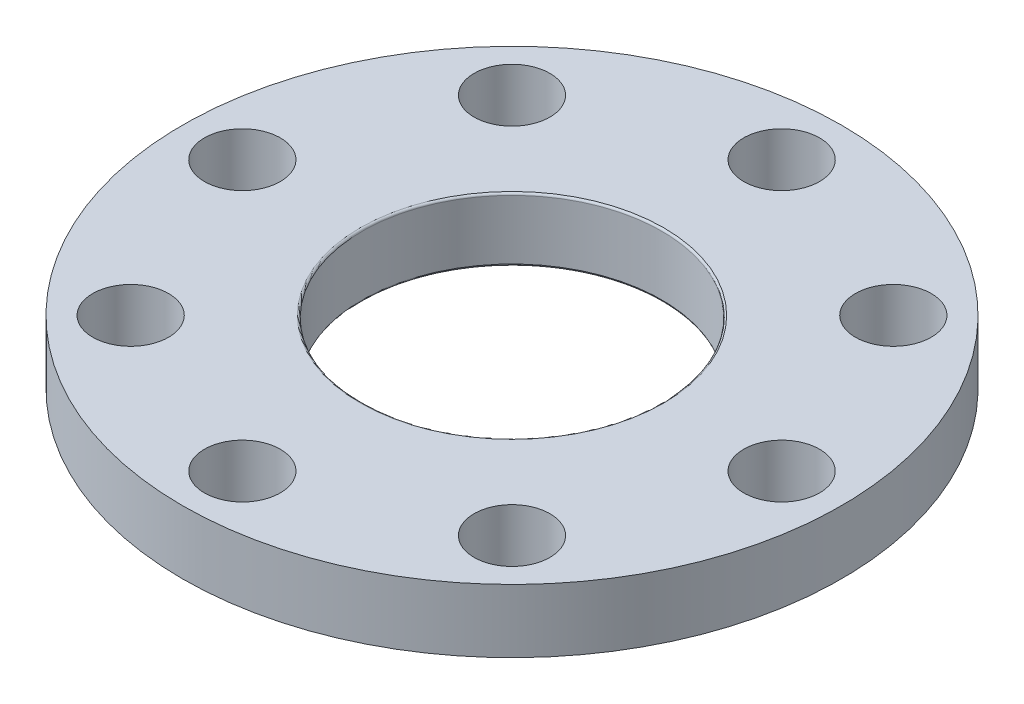
SolidWorks part; units mm, degrees
ref_plane "Front Plane" through (0, 0, 0) normal (0, 0, 1) x (1, 0, 0)
ref_plane "Top Plane" through (0, 0, 0) normal (0, 1, 0) x (1, 0, 0)
ref_plane "Right Plane" through (0, 0, 0) normal (1, 0, 0) x (0, 0, -1)
sketch "Sketch1" plane through (0, 0, 0) normal (0, 1, 0) x (1, 0, 0)
  circle A0 centre (0, 0) radius 16.5
  circle A1 centre (0, 0) radius 7.5
  dimension "D1" = 15
  dimension "D2" = 33
extrude "Boss-Extrude1" add sketch "Sketch1" along normal blind 3.175
fillet "Fillet1" radius 0.1 2 edges at (0, 0, 7.5) (0, 3.175, 7.5)
sketch "Sketch2" plane through (0, 3.175, 0) normal (0, 1, 0) x (-1, 0, 0)
  circle A0 centre (0, -13.5) radius 1.8986
  dimension "D2" = 3.7973
  dimension "D1" = 13.5
extrude "Cut-Extrude1" cut sketch "Sketch2" against normal through all
pattern_circular "CirPattern1" count 8 over 360 about axis through (0, 0, 0) along (0, 1, 0) of "Cut-Extrude1"
